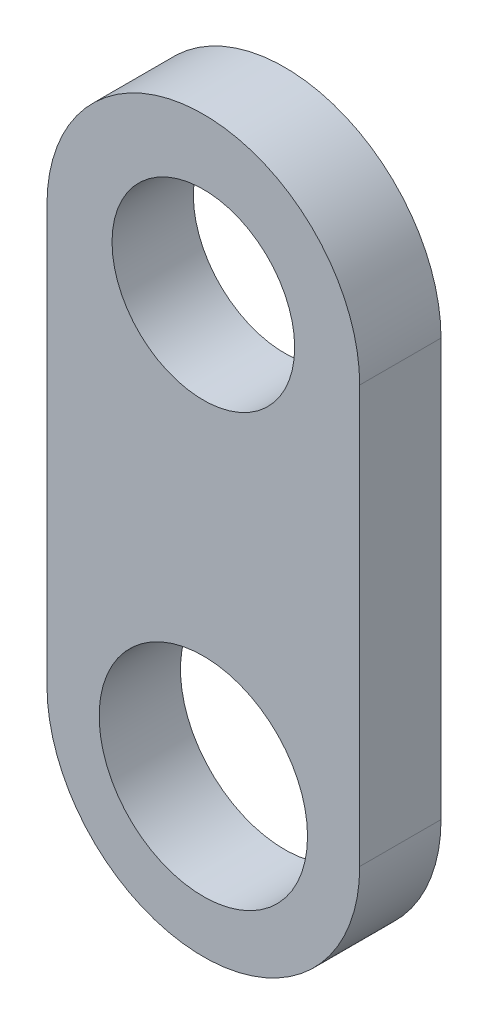
SolidWorks part; units mm, degrees
material "6061-T6 (SS)"
ref_plane "Front Plane" through (0, 0, 0) normal (0, 0, 1) x (1, 0, 0)
ref_plane "Top Plane" through (0, 0, 0) normal (0, 1, 0) x (1, 0, 0)
ref_plane "Right Plane" through (0, 0, 0) normal (1, 0, 0) x (0, 0, -1)
sketch "Sketch2" plane through (0, 0, 0) normal (0, 0, 1) x (1, 0, 0)
  line L0 (0, 0) -> (0, 50.8) construction
  line L1 (-19.05, 0) -> (-19.05, 50.8)
  line L2 (19.05, 0) -> (19.05, 50.8)
  arc A0 (-19.05, 0) -> (19.05, 0) centre (0, 0) ccw
  arc A1 (19.05, 50.8) -> (-19.05, 50.8) centre (0, 50.8) ccw
  circle A2 centre (0, 50.8) radius 11.1252
  circle A3 centre (0, 0) radius 12.6937
  point P3 (0, 25.4)
  dimension "D3" = 22.2504
  dimension "D4" = 25.3873
  dimension "D1" = 38.1
  dimension "D2" = 50.8
extrude "Boss-Extrude1" add sketch "Sketch2" along normal mid plane 9.906
equation "\"Link Width\"= 1.5in"
equation "\"Hole Spacing\"= 2in"
equation "\"Link Thickness\" = 0.39in"
equation "\"Bracket Bar Diameter\"= \"Bar Diameter\""
equation "\"Second Shaft Diameter\"= 1in"
equation "\"D1@Sketch2\"=\"Link Width\""
equation "\"D2@Sketch2\"=\"Hole Spacing\""
equation "\"D1@Boss-Extrude1\"=\"Link Thickness\""
equation "\"D3@Sketch2\" = \"Bracket Hole Diameter\""
equation "\"D4@Sketch2\" = \"Shaft Hole Diameter\""
equation "\"Bar Diameter\" = \"Minimum Bar Diameter\"+\"Diameter Allowance\""
equation "\"Bracket Hole Diameter\"= \"Bracket Bar Diameter\" + 0.001in"
equation "\"Shaft Hole Diameter\"= \"Second Shaft Diameter\" - 0.0005in"
